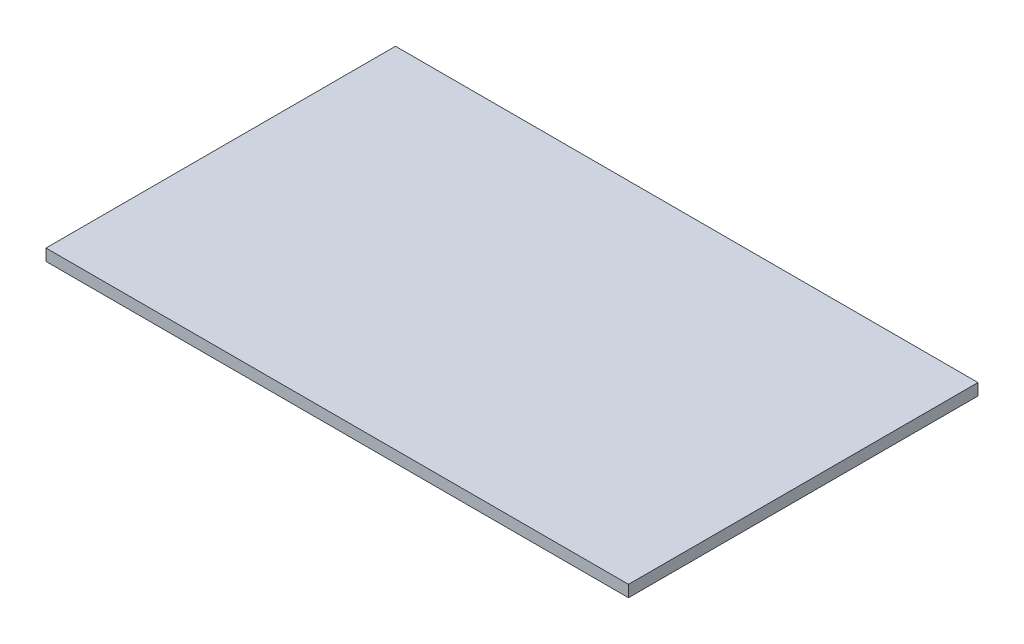
SolidWorks part; units mm, degrees
ref_plane "Front Plane" through (0, 0, 0) normal (0, 0, 1) x (1, 0, 0)
ref_plane "Top Plane" through (0, 0, 0) normal (0, 1, 0) x (1, 0, 0)
ref_plane "Right Plane" through (0, 0, 0) normal (1, 0, 0) x (0, 0, -1)
sketch "Sketch1" plane through (0, 0, 0) normal (0, 1, 0) x (1, 0, 0)
  line L1 (-54.3842, 257.5375) -> (445.6158, 257.5375)
  line L2 (-54.3842, 257.5375) -> (-54.3842, -42.4625)
  line L3 (-54.3842, -42.4625) -> (445.6158, -42.4625)
  line L4 (445.6158, 257.5375) -> (445.6158, -42.4625)
extrude "Boss-Extrude1" add sketch "Sketch1" along normal blind 10
